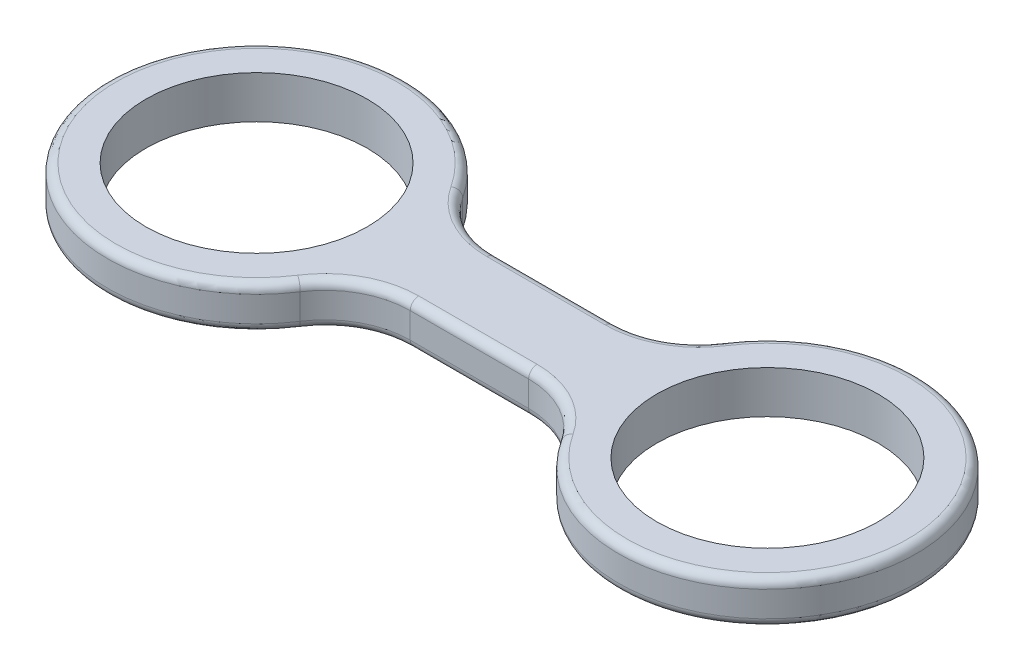
SolidWorks part; units mm, degrees
ref_plane "Front Plane" through (0, 0, 0) normal (0, 0, 1) x (1, 0, 0)
ref_plane "Top Plane" through (0, 0, 0) normal (0, 1, 0) x (1, 0, 0)
ref_plane "Right Plane" through (0, 0, 0) normal (1, 0, 0) x (0, 0, -1)
sketch "Sketch1" plane through (0, 0, 0) normal (0, 1, 0) x (1, 0, 0)
  line L0 (0, 0) -> (60, 0) construction
  line L1 (16.7705, 5) -> (43.2295, 5)
  line L2 (16.7705, -5) -> (43.2295, -5)
  circle A0 centre (0, 0) radius 13
  circle A1 centre (60, 0) radius 13
  arc A2 (16.7705, 5) -> (16.7705, -5) centre (0, 0) ccw
  arc A3 (43.2295, -5) -> (43.2295, 5) centre (60, 0) ccw
  dimension "D2" = 26
  dimension "D3" = 26
  dimension "D4" = 35
  dimension "D5" = 35
  dimension "D1" = 60
  dimension "D6" = 5
  dimension "D7" = 5
extrude "Boss-Extrude1" add sketch "Sketch1" along normal blind 5
fillet "Fillet1" radius 10 4 edges at (43.2295, 2.5, 5) (16.7705, 2.5, 5) (43.2295, 2.5, -5) (16.7705, 2.5, -5)
fillet "Fillet2" radius 1 16 edges at (18.2815, 5, -6.2095) (30, 5, -5) (41.7185, 5, -6.2095) (77.5, 5, 0) (41.7185, 5, 6.2095) (30, 5, 5) (18.2815, 5, 6.2095) (18.2815, 0, 6.2095) (30, 0, 5) (41.7185, 0, 6.2095) (77.5, 0, 0) (41.7185, 0, -6.2095) (30, 0, -5) (18.2815, 0, -6.2095) (-17.5, 0, 0) (-17.5, 5, 0)
